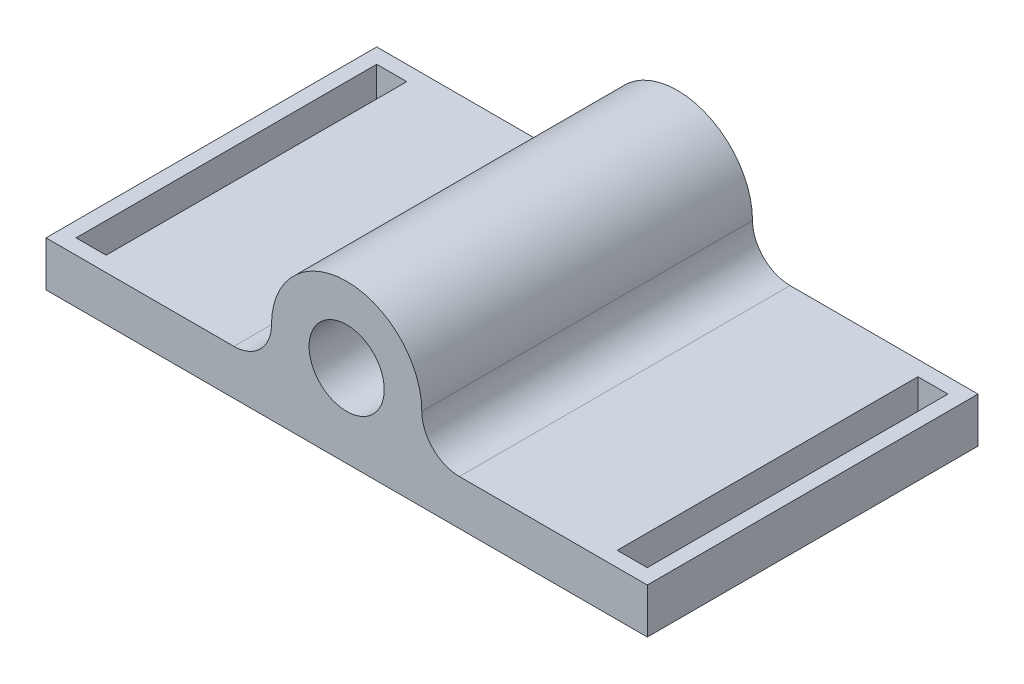
SolidWorks part; units mm, degrees
ref_plane "Front Plane" through (0, 0, 0) normal (0, 0, 1) x (1, 0, 0)
ref_plane "Top Plane" through (0, 0, 0) normal (0, 1, 0) x (1, 0, 0)
ref_plane "Right Plane" through (0, 0, 0) normal (1, 0, 0) x (0, 0, -1)
sketch "Sketch1" plane through (0, 0, 0) normal (0, 0, 1) x (1, 0, 0)
  line L0 (-27.5, 4.6307) -> (12.5, 4.6307)
  line L1 (-27.5, 4.6307) -> (-27.5, 7.6307)
  line L2 (12.5, 4.6307) -> (12.5, 7.6307)
  line L3 (-27.5, 7.6307) -> (-15, 7.6307)
  line L4 (12.5, 7.6307) -> (0, 7.6307)
  arc A0 (-15, 7.6307) -> (-12.5, 10.1307) centre (-15, 10.1307) ccw
  arc A1 (0, 7.6307) -> (-2.5, 10.1307) centre (0, 10.1307) cw
  arc A2 (-2.5, 10.1307) -> (-12.5, 10.1307) centre (-7.5, 10.1307) ccw
  circle A3 centre (-7.5, 10.1307) radius 2.5
  dimension "D1" = 40
  dimension "D2" = 3
  dimension "D3" = 3
  dimension "D4" = 12.5
  dimension "D5" = 12.5
  dimension "D6" = 2.5
  dimension "D7" = 2.5
extrude "Boss-Extrude1" add sketch "Sketch1" along normal blind 22
sketch "Sketch3" plane through (0, 7.6307, 0) normal (0, 1, 0) x (1, 0, 0)
  line L0 (-15, 0) -> (-27.5, 0) construction
  line L1 (-26.5, -1) -> (-24.5, -1)
  line L2 (-26.5, -1) -> (-26.5, -21)
  line L3 (-26.5, -21) -> (-24.5, -21)
  line L4 (-24.5, -1) -> (-24.5, -21)
  line L5 (-27.5, -22) -> (-27.5, 0) construction
  line L6 (12.5, -22) -> (12.5, 0) construction
  line L7 (9.5, -1) -> (11.5, -1)
  line L8 (9.5, -1) -> (9.5, -21)
  line L9 (9.5, -21) -> (11.5, -21)
  line L10 (11.5, -1) -> (11.5, -21)
  line L11 (12.5, 0) -> (0, 0) construction
  dimension "D1" = 20
  dimension "D2" = 1
  dimension "D3" = 2
  dimension "D4" = 1
  dimension "D5" = 2
  dimension "D6" = 20
  dimension "D7" = 1
  dimension "D8" = 1
extrude "Cut-Extrude1" cut sketch "Sketch3" against normal blind 15
